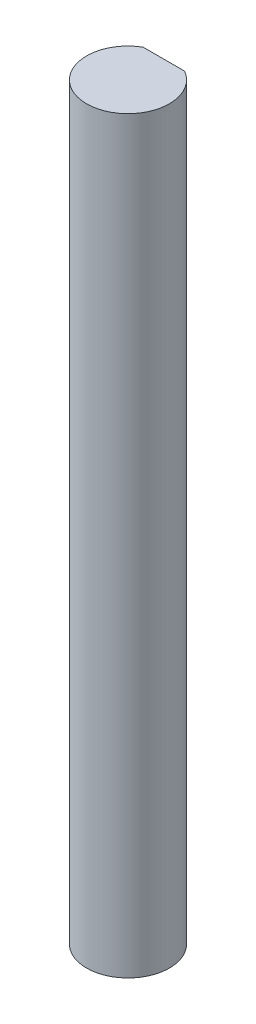
SolidWorks part; units mm, degrees
material "Custom Plastic"
ref_plane "X-Y Datum" through (0, 0, 0) normal (0, 0, 1) x (1, 0, 0)
ref_plane "X-Z Datum" through (0, 0, 0) normal (0, 1, 0) x (1, 0, 0)
ref_plane "Y-Z Datum" through (0, 0, 0) normal (1, 0, 0) x (0, 0, -1)
sketch "Sketch1" plane through (0, 0, 0) normal (0, 1, 0) x (1, 0, 0)
  line L0 (-2.3876, 4.1208) -> (2.3876, 4.1208)
  circle A0 centre (0, 0) radius 4.7625
  dimension "D1" = 9.525
  dimension "D2" = 4.7752
extrude "Boss-Extrude1" add sketch "Sketch1" along normal blind 43 and the other way blind 43 contours L0 A0
